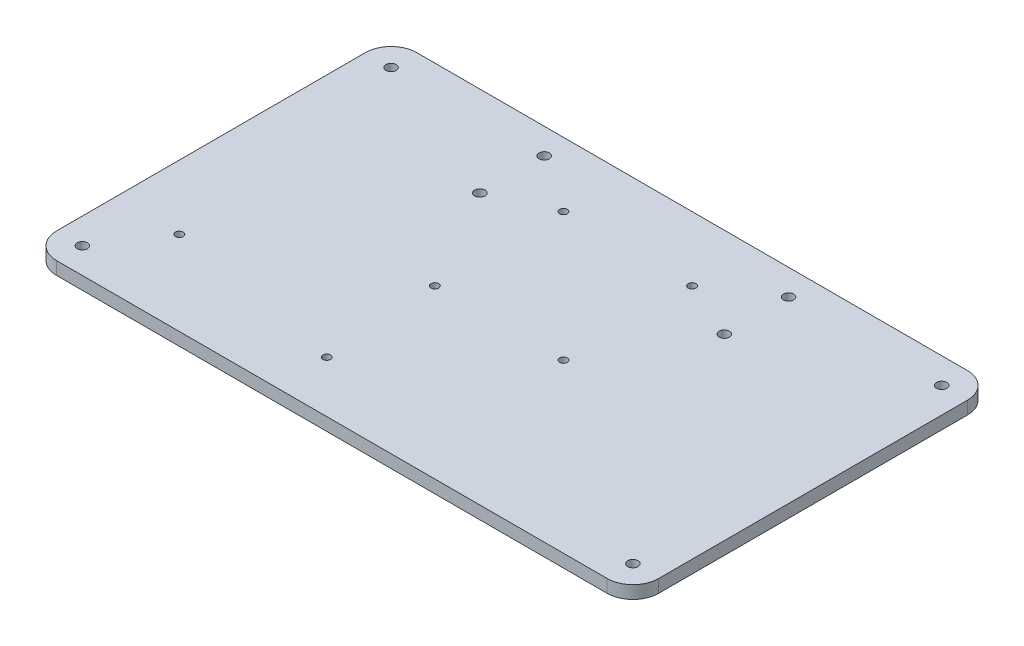
SolidWorks part; units mm, degrees
ref_plane "前视基准面" through (0, 0, 0) normal (0, 0, 1) x (1, 0, 0)
ref_plane "上视基准面" through (0, 0, 0) normal (0, 1, 0) x (1, 0, 0)
ref_plane "右视基准面" through (0, 0, 0) normal (1, 0, 0) x (0, 0, -1)
other "质心 (COM)"
sketch "草图1" plane through (0, 0, 0) normal (0, 1, 0) x (1, 0, 0)
  line L1 (117, -70) -> (-117, -70)
  line L2 (117, -70) -> (117, 70)
  line L3 (117, 70) -> (-117, 70)
  line L4 (-117, -70) -> (-117, 70)
  line L5 (117, -70) -> (-117, 70) construction
  line L6 (117, 70) -> (-117, -70) construction
  point P0 (0, 0)
  dimension "D1" = 234
  dimension "D2" = 140
extrude "凸台-拉伸1" add sketch "草图1" along normal blind 5
sketch "草图2" plane through (0, 5, 0) normal (0, 1, 0) x (1, 0, 0)
  line L0 (-117, 70) -> (-117, -70) construction
  line L1 (-117, -70) -> (117, -70) construction
  line L2 (117, -70) -> (117, 70) construction
  line L3 (117, 70) -> (-117, 70) construction
  circle A0 centre (-107, 60) radius 2
  circle A1 centre (107, 60) radius 2
  circle A2 centre (107, -60) radius 2
  circle A3 centre (-107, -60) radius 2
  dimension "D1" = 4
  dimension "D2" = 10
  dimension "D3" = 10
  dimension "D4" = 120
  dimension "D5" = 120
  dimension "D6" = 10
  dimension "D7" = 10
  dimension "D8" = 4
  dimension "D9" = 4
  dimension "D10" = 4
  dimension "D11" = 10
  dimension "D12" = 10
extrude "切除-拉伸1" cut sketch "草图2" against normal blind 5
fillet "圆角1" radius 10 4 edges at (-117, 2.5, 70) (-117, 2.5, -70) (117, 2.5, -70) (117, 2.5, 70)
sketch "草图3" plane through (0, 5, 0) normal (0, 1, 0) x (1, 0, 0)
  line L0 (107, 70) -> (-107, 70) construction
  circle A0 centre (-47.5, 60) radius 2
  circle A1 centre (47.5, 60) radius 2
  circle A2 centre (47.5, 35) radius 2
  circle A3 centre (-47.5, 35) radius 2
  dimension "D1" = 95
  dimension "D2" = 95
  dimension "D3" = 25
  dimension "D4" = 25
  dimension "D5" = 47.5
  dimension "D6" = 10
  dimension "D7" = 4
  dimension "D8" = 4
  dimension "D9" = 4
  dimension "D10" = 4
  dimension "D11" = 10
extrude "切除-拉伸2" cut sketch "草图3" against normal blind 20
sketch "草图4" plane through (0, 5, 0) normal (0, 1, 0) x (1, 0, 0)
  circle A0 centre (-25, 45) radius 1.5
  circle A1 centre (25, 45) radius 1.5
  circle A2 centre (25, -5) radius 1.5
  circle A3 centre (-25, -5) radius 1.5
  circle A4 centre (-47.5, 35) radius 2 construction
  circle A5 centre (47.5, 35) radius 2 construction
  dimension "D1" = 50
  dimension "D2" = 50
  dimension "D3" = 50
  dimension "D4" = 50
  dimension "D5" = 25
  dimension "D6" = 25
  dimension "D7" = 3
  dimension "D8" = 3
  dimension "D9" = 3
  dimension "D10" = 3
  dimension "D11" = 10
  dimension "D12" = 10
extrude "切除-拉伸3" cut sketch "草图4" against normal blind 10
sketch "草图5" plane through (0, 5, 0) normal (0, 1, 0) x (1, 0, 0)
  line L0 (-107, -70) -> (107, -70) construction
  line L1 (-117, 60) -> (-117, -60) construction
  circle A0 centre (-92, -37.3) radius 1.5
  circle A1 centre (-22, -50) radius 1.5
  dimension "D1" = 70
  dimension "D2" = 12.7
  dimension "D3" = 32.7
  dimension "D4" = 25
  dimension "D5" = 3
  dimension "D6" = 3
extrude "切除-拉伸4" cut sketch "草图5" against normal blind 10
